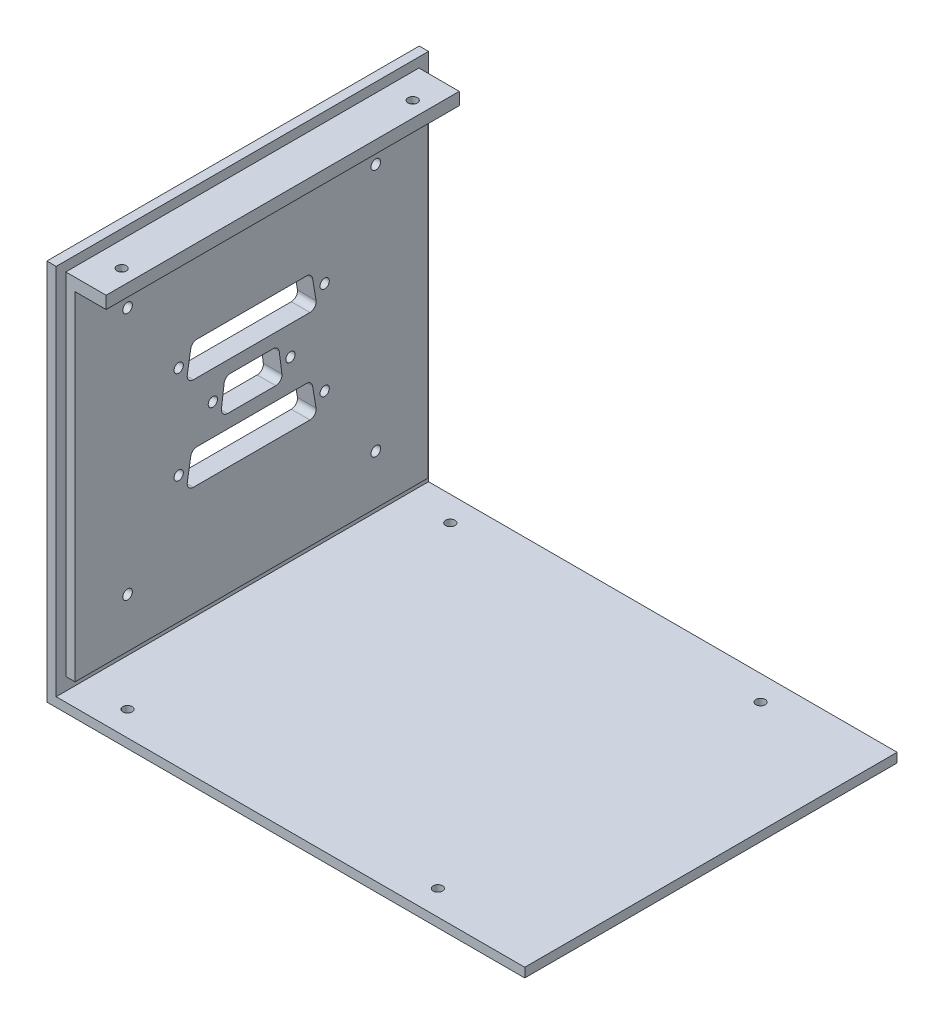
SolidWorks part; units mm, degrees
other "Markup1"
sketch "Sketch5" plane through (-105, 0, 60.5) normal (-0.0451, -0.9984, 0.0353) x (-0.7444, 0.01, -0.6676)
other "Markup2"
sketch "Sketch6" plane through (97, 11, -60) normal (0.0014, 0.7787, -0.6274) x (0.9996, 0.0165, 0.0227)
ref_plane "Front Plane" through (0, 0, 0) normal (0, 0, 1) x (1, 0, 0)
ref_plane "Top Plane" through (0, 0, 0) normal (0, 1, 0) x (1, 0, 0)
ref_plane "Right Plane" through (0, 0, 0) normal (1, 0, 0) x (0, 0, -1)
sketch "Sketch1" plane through (0, 0, 0) normal (0, 1, 0) x (1, 0, 0)
  line L1 (-77, 60) -> (77, 60)
  line L2 (-77, 60) -> (-77, -60)
  line L3 (-77, -60) -> (77, -60)
  line L4 (77, 60) -> (77, -60)
  point P4 (0, 60)
  point P5 (-77, 0)
  dimension "D1" = 120
  dimension "D2" = 154
extrude "Large-Wall-Outer" add sketch "Sketch1" along normal blind 3
sketch "Sketch8" plane through (0, 3, 0) normal (0, 1, 0) x (1, 0, 0)
  line L0 (-77, -60) -> (77, -60) construction
  line L1 (-77, 60) -> (-74, 60)
  line L2 (-77, 60) -> (-77, -60)
  line L3 (-77, -60) -> (-74, -60)
  line L4 (-74, 60) -> (-74, -60)
  dimension "D1" = 3
extrude "Small-Wall-Outer" add sketch "Sketch8" along normal blind 120.1
sketch "Sketch10" plane through (-74, 0, 0) normal (1, 0, 0) x (0, 0, -1)
  line L1 (-56.9, 7.1) -> (56.9, 7.1)
  line L2 (-56.9, 7.1) -> (-56.9, 120)
  line L3 (-56.9, 120) -> (56.9, 120)
  line L4 (56.9, 7.1) -> (56.9, 120)
  point P4 (0, 120)
  dimension "D1" = 112.9
  dimension "D2" = 113.8
  dimension "D3" = 3.1
extrude "Small-Wall-Inner" add sketch "Sketch10" along normal blind 3
sketch "Sketch14" plane through (-71, 0, 0) normal (1, 0, 0) x (0, 0, -1)
  line L1 (56.9, 116) -> (-56.9, 116)
  line L2 (56.9, 116) -> (56.9, 120)
  line L3 (56.9, 120) -> (-56.9, 120)
  line L4 (-56.9, 116) -> (-56.9, 120)
  dimension "D1" = 4
extrude "Mount" add sketch "Sketch14" along normal blind 10
sketch "Sketch17" plane through (0, 116, 0) normal (0, -1, 0) x (1, 0, 0)
  line L0 (-61, 56.9) -> (-71, 56.9) construction
  line L1 (-66, 43.7) -> (-63.2287, 45.3)
  line L2 (-63.2287, 45.3) -> (-63.2287, 48.5)
  line L3 (-63.2287, 48.5) -> (-66, 50.1)
  line L4 (-66, 50.1) -> (-68.7713, 48.5)
  line L5 (-68.7713, 48.5) -> (-68.7713, 45.3)
  line L6 (-68.7713, 45.3) -> (-66, 43.7)
  line L7 (-61, -56.9) -> (-71, -56.9) construction
  line L8 (-66, -50.1) -> (-63.2287, -48.5)
  line L9 (-63.2287, -48.5) -> (-63.2287, -45.3)
  line L10 (-63.2287, -45.3) -> (-66, -43.7)
  line L11 (-66, -43.7) -> (-68.7713, -45.3)
  line L12 (-68.7713, -45.3) -> (-68.7713, -48.5)
  line L13 (-68.7713, -48.5) -> (-66, -50.1)
  circle A0 centre (-66, 46.9) radius 3.2 construction
  circle A1 centre (-66, -46.9) radius 3.2 construction
  point P12 (-66, -56.9)
  point P16 (-66, 56.9)
  dimension "D1" = 10
  dimension "D3" = 6.4
  dimension "D4" = 6.4
  dimension "D2" = 10
extrude "Mounting-Nuts" cut sketch "Sketch17" against normal blind 2
sketch "Sketch18" plane through (0, 118, 0) normal (0, -1, 0) x (1, 0, 0)
  line L0 (-68.7713, 48.5) -> (-68.7713, 45.3) construction
  circle A0 centre (-66, 46.9) radius 1.5
  point P8 (-68.7713, 46.9)
  dimension "D1" = 3
extrude "Nut-1-Bolt-Hole" cut sketch "Sketch18" against normal up to next
sketch "Sketch19" plane through (0, 118, 0) normal (0, -1, 0) x (1, 0, 0)
  line L0 (-68.7713, -45.3) -> (-68.7713, -48.5) construction
  circle A0 centre (-66, -46.9) radius 1.5
  point P6 (-68.7713, -46.9)
  dimension "D1" = 3
extrude "Nut-2-Bolt-Hole" cut sketch "Sketch19" against normal up to next
sketch "Sketch23" plane through (-77, 0, 0) normal (-1, 0, 0) x (0, 0, -1)
  line L0 (-12.5, -63.05) -> (12.5, -63.05) construction
  line L1 (-23.52, -78.05) -> (23.52, -78.05) construction
  line L2 (-6.8916, -68.1679) -> (6.8916, -68.1679)
  line L4 (-7.7666, -57.4179) -> (7.7666, -57.4179)
  line L6 (-17.6522, -83.0962) -> (17.6522, -83.0962)
  line L8 (-18.7772, -72.3462) -> (18.7772, -72.3462)
  line L10 (-23.52, -48.05) -> (23.52, -48.05) construction
  line L11 (-17.6522, -53.0962) -> (17.6522, -53.0962)
  line L13 (-18.7772, -42.3462) -> (18.7772, -42.3462)
  line L16 (-19.625, -51.425) -> (-20.75, -44.675)
  line L19 (20.75, -44.675) -> (19.625, -51.425)
  line L22 (-8.875, -66.425) -> (-9.75, -59.675)
  line L25 (9.75, -59.675) -> (8.875, -66.425)
  line L28 (-20.75, -74.675) -> (-19.625, -81.425)
  line L31 (19.625, -81.425) -> (20.75, -74.675)
  line L32 (60, -123.1) -> (-60, -123.1) construction
  line L34 (60, -123.1) -> (60, -3) construction
  circle A0 centre (-12.5, -63.05) radius 1.5
  circle A1 centre (12.5, -63.05) radius 1.5
  circle A2 centre (-23.52, -78.05) radius 1.5
  circle A3 centre (23.52, -78.05) radius 1.5
  circle A4 centre (-23.52, -48.05) radius 1.5
  circle A5 centre (23.52, -48.05) radius 1.5
  arc A6 (18.7772, -42.3462) -> (20.75, -44.675) centre (18.7772, -44.3462) cw
  arc A7 (-18.7772, -42.3462) -> (-20.75, -44.675) centre (-18.7772, -44.3462) ccw
  arc A8 (17.6522, -53.0962) -> (19.625, -51.425) centre (17.6522, -51.0962) ccw
  arc A9 (-17.6522, -53.0962) -> (-19.625, -51.425) centre (-17.6522, -51.0962) cw
  arc A10 (20.75, -74.675) -> (18.7772, -72.3462) centre (18.7772, -74.3462) ccw
  arc A11 (17.6522, -83.0962) -> (19.625, -81.425) centre (17.6522, -81.0962) ccw
  arc A12 (-19.625, -81.425) -> (-17.6522, -83.0962) centre (-17.6522, -81.0962) ccw
  arc A13 (-20.75, -74.675) -> (-18.7772, -72.3462) centre (-18.7772, -74.3462) cw
  arc A14 (7.7666, -57.4179) -> (9.75, -59.675) centre (7.7666, -59.4179) cw
  arc A15 (8.875, -66.425) -> (6.8916, -68.1679) centre (6.8916, -66.1679) cw
  arc A16 (-8.875, -66.425) -> (-6.8916, -68.1679) centre (-6.8916, -66.1679) ccw
  arc A17 (-9.75, -59.675) -> (-7.7666, -57.4179) centre (-7.7666, -59.4179) cw
  point P4 (0, -63.05)
  point P8 (0, -123.1)
  point P9 (0, -57.4179)
  point P17 (0, -78.05)
  point P19 (60, -63.05)
  point P23 (-9.3125, -63.05)
  point P24 (0, -83.0962)
  point P29 (0, -63.05)
  point P38 (20.1875, -78.05)
  point P39 (-20.1875, -48.05)
  point P41 (9.3125, -63.05)
  point P42 (20.1875, -48.05)
  point P45 (-20.1875, -78.05)
  point P52 (21.1381, -42.3462)
  point P59 (19.3465, -53.0962)
  point P66 (21.1381, -72.3462)
  point P69 (19.3465, -83.0962)
  point P76 (10.0426, -57.4179)
  point P79 (8.6491, -68.1679)
  dimension "D1" = 3
  dimension "D2" = 3
  dimension "D8" = 3
  dimension "D7" = 3
  dimension "D14" = 3
  dimension "D15" = 3
  dimension "D4" = 41.5
  dimension "D5" = 11.02
  dimension "D21" = 2
  dimension "D25" = 2
  dimension "D27" = 2
  dimension "D3" = 25
  dimension "D6" = 10.75
  dimension "D9" = 47.04
  dimension "D13" = 15
  dimension "D18" = 10.75
  dimension "D19" = 15
  dimension "D20" = 10.75
  dimension "D28" = 39.25
  dimension "D30" = 41.5
  dimension "D31" = 39.25
  dimension "D32" = 19.5
  dimension "D33" = 17.75
extrude "Connector-Slots" cut sketch "Sketch23" against normal up to next
sketch "Sketch27" plane through (-77, 0, 0) normal (-1, 0, 0) x (0, 0, 1)
  line L0 (-60, 0) -> (60, 0) construction
  circle A0 centre (-40, 23.05) radius 1.55
  circle A2 centre (12.5, 63.05) radius 1.5 construction
  circle A3 centre (-12.5, 63.05) radius 1.5 construction
  circle A4 centre (12.5, 63.05) radius 1.5
  circle A5 centre (-12.5, 63.05) radius 1.5
  circle A6 centre (40, 23.05) radius 1.55
  circle A7 centre (40, 103.05) radius 1.55
  circle A8 centre (-40, 103.05) radius 1.55
  point P12 (0, 63.05)
  point P15 (0, 0)
  dimension "D1" = 3.1
  dimension "D2" = 40
  dimension "D3" = 40
  dimension "D4" = 2
  dimension "D5" = 2
extrude "PCB-Mount-Holes" cut sketch "Sketch27" against normal up to next (6 mm away)
sketch "Sketch28" plane through (0, 3, 0) normal (0, 1, 0) x (1, 0, 0)
  line L0 (-77, -60) -> (77, -60) construction
  line L1 (-77, 60) -> (-77, -60) construction
  circle A0 centre (-59, -52) radius 1.5
  point P2 (0, 0)
  point P3 (0, 0)
  point P8 (0, 0)
  dimension "D1" = 8
  dimension "D2" = 18
extrude "bolt-hole1" cut sketch "Sketch28" against normal blind 10
sketch "Sketch29" plane through (0, 0, 0) normal (0, -1, 0) x (-1, 0, 0)
  line L0 (77, -60) -> (-77, -60) construction
  line L1 (-77, -60) -> (-77, 60) construction
  circle A0 centre (-41, -52) radius 1.5
  point P2 (0, 0)
  dimension "D1" = 8
  dimension "D2" = 36
extrude "bolt-hole2" cut sketch "Sketch29" against normal blind 10
sketch "Sketch30" plane through (0, 0, 0) normal (0, -1, 0) x (1, 0, 0)
  line L0 (-77, -60) -> (-77, 60) construction
  line L1 (77, -60) -> (-77, -60) construction
  line L2 (77, 60) -> (77, -60) construction
  circle A0 centre (-59, -52) radius 1.5
  circle A1 centre (41, -52) radius 1.5
  dimension "D1" = 18
  dimension "D3" = 8
  dimension "D2" = 8
  dimension "D4" = 36
extrude "bolt-holes34" cut sketch "Sketch30" against normal blind 10
